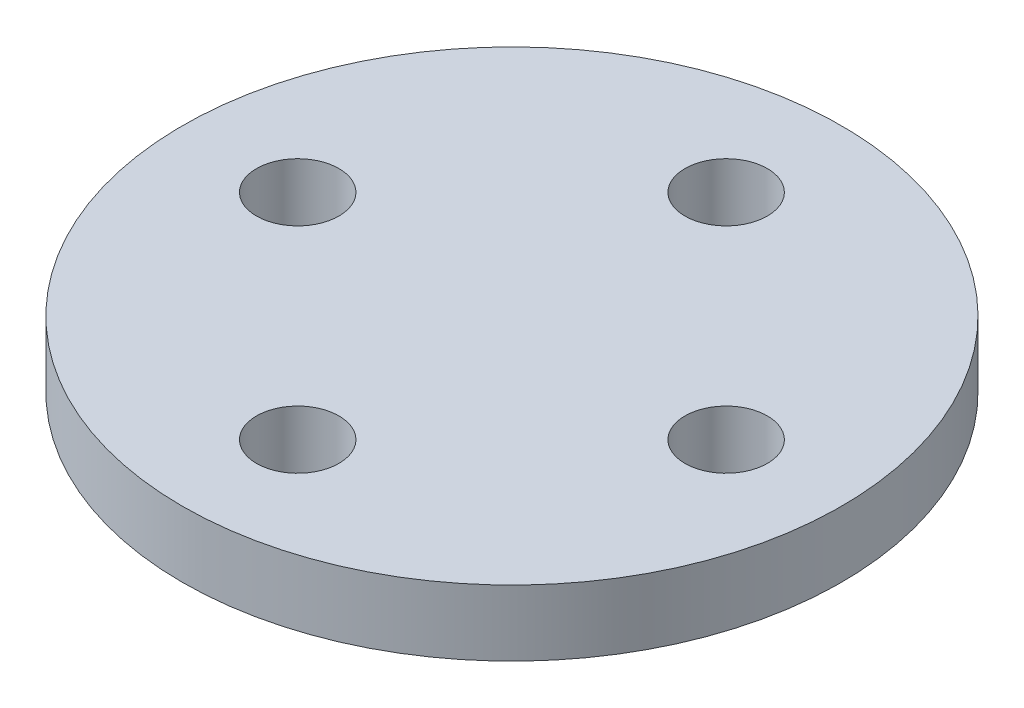
SolidWorks part; units mm, degrees
ref_plane "前视基准面" through (0, 0, 0) normal (0, 0, 1) x (1, 0, 0)
ref_plane "上视基准面" through (0, 0, 0) normal (0, 1, 0) x (1, 0, 0)
ref_plane "右视基准面" through (0, 0, 0) normal (1, 0, 0) x (0, 0, -1)
other "Configuration Table"
sketch "草图1" plane through (0, 0, 0) normal (0, 1, 0) x (1, 0, 0)
  line L0 (-20.3948, 0) -> (20.6192, 0) construction
  line L1 (0, 20.8161) -> (0, -16.9428) construction
  circle A0 centre (0, 0) radius 10
  circle A1 centre (0, 6.5) radius 1.25
  circle A2 centre (6.5, 0) radius 1.25
  circle A3 centre (0, -6.5) radius 1.25
  circle A4 centre (-6.5, 0) radius 1.25
  point P18 (0, 0)
  dimension "D1" = 20
  dimension "D2" = 2.5
  dimension "D3" = 6.5
  dimension "D4" = 4
extrude "凸台-拉伸1" add sketch "草图1" along normal blind 2
sketch "草图2" plane through (0, 0, 0) normal (0, -1, 0) x (1, 0, 0)
  circle A0 centre (0, 0) radius 4.5
  dimension "D1" = 9
extrude "凸台-拉伸2" add sketch "草图2" along normal blind 2
sketch "草图3" plane through (0, -2, 0) normal (0, -1, 0) x (1, 0, 0)
  circle A0 centre (0, 0) radius 2.5
  dimension "D1" = 5
extrude "切除-拉伸1" cut sketch "草图3" against normal blind 2
